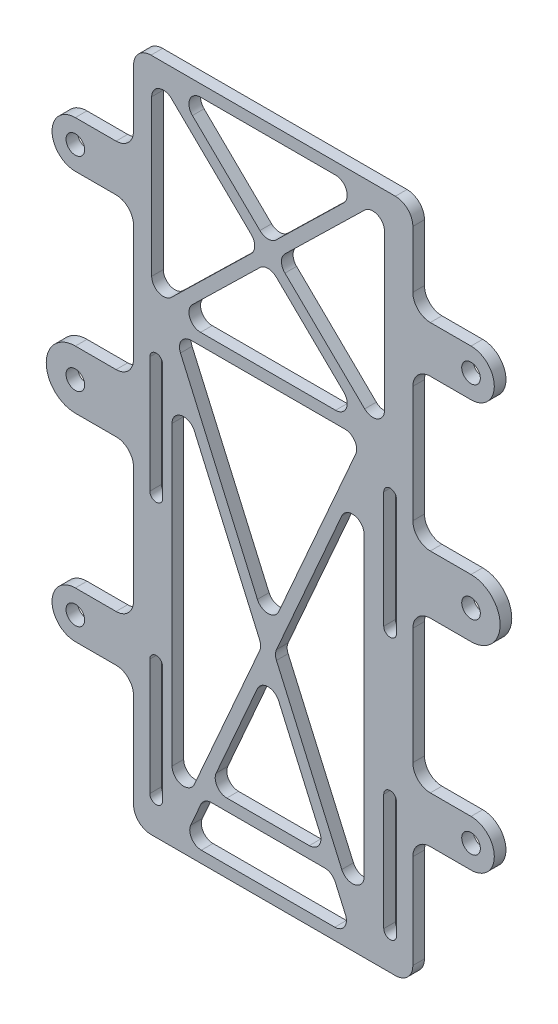
SolidWorks part; units mm, degrees
material "A-玻璃纤维"
ref_plane "前视基准面" through (0, 0, 0) normal (0, 0, 1) x (1, 0, 0)
ref_plane "上视基准面" through (0, 0, 0) normal (0, 1, 0) x (1, 0, 0)
ref_plane "右视基准面" through (0, 0, 0) normal (1, 0, 0) x (0, 0, -1)
sketch "草图1" plane through (0, 0, 0) normal (0, 0, 1) x (1, 0, 0)
  line L0 (-20.1, -32) -> (-20.1, -52) construction
  line L1 (24, 58) -> (-24, 58)
  line L2 (24, 58) -> (24, -58)
  line L3 (24, -58) -> (-24, -58)
  line L4 (-24, 58) -> (-24, -58)
  line L5 (24, 58) -> (-24, -58) construction
  line L6 (24, -58) -> (-24, 58) construction
  line L7 (-19, -32) -> (-19, -52)
  line L8 (-21.2, -32) -> (-21.2, -52)
  line L9 (20.1, -32) -> (20.1, -52) construction
  line L10 (19, -32) -> (19, -52)
  line L11 (21.2, -32) -> (21.2, -52)
  line L12 (-20.1, 13) -> (-20.1, -7) construction
  line L13 (-19, 13) -> (-19, -7)
  line L14 (-21.2, 13) -> (-21.2, -7)
  line L15 (20.1, 13) -> (20.1, -7) construction
  line L16 (19, 13) -> (19, -7)
  line L17 (21.2, 13) -> (21.2, -7)
  line L18 (0, 97.0381) -> (0, -100.4678) construction
  arc A0 (-19, -32) -> (-21.2, -32) centre (-20.1, -32) ccw
  arc A1 (-21.2, -52) -> (-19, -52) centre (-20.1, -52) ccw
  arc A2 (19, -32) -> (21.2, -32) centre (20.1, -32) cw
  arc A3 (21.2, -52) -> (19, -52) centre (20.1, -52) cw
  arc A4 (-19, 13) -> (-21.2, 13) centre (-20.1, 13) ccw
  arc A5 (-21.2, -7) -> (-19, -7) centre (-20.1, -7) ccw
  arc A6 (19, 13) -> (21.2, 13) centre (20.1, 13) cw
  arc A7 (21.2, -7) -> (19, -7) centre (20.1, -7) cw
  point P0 (0, 0)
  point P8 (-20.1, -42)
  point P16 (20.1, -42)
  point P20 (-20.1, 3)
  point P30 (20.1, 3)
  dimension "D1" = 48
  dimension "D2" = 116
  dimension "D3" = 20
  dimension "D4" = 20
  dimension "D5" = 20.1
  dimension "D6" = 65
  dimension "D7" = 2.2
  dimension "D8" = 2.2
  dimension "D9" = 6
extrude "凸台-拉伸1" add sketch "草图1" along normal blind 2
sketch "草图3" plane through (0, 0, 2) normal (0, 0, 1) x (1, 0, 0)
  line L0 (-24, -58) -> (24, -58) construction
  line L1 (12.3424, 19) -> (-14.1024, 19)
  line L2 (15.62, 5.0055) -> (15.62, -46.0055)
  line L3 (10.5824, -56) -> (-12.3424, -56)
  line L4 (-17.38, 5.0055) -> (-17.38, -46.0055)
  line L5 (16.5, 17) -> (-16.5, -58) construction
  line L6 (16.5, -58) -> (-16.5, 17) construction
  line L7 (24, 58) -> (-24, 58) construction
  line L8 (10.7201, 56) -> (-12.4801, 56)
  line L9 (19.12, 51.8601) -> (19.12, 25.1399)
  line L10 (10.7201, 21) -> (-12.4801, 21)
  line L11 (-20.88, 51.8601) -> (-20.88, 25.1399)
  line L12 (20, 58) -> (-20, 19) construction
  line L13 (0.5162, 41.2579) -> (12.1163, 52.568)
  line L14 (20, 19) -> (-20, 58) construction
  line L15 (0.9506, -27.1435) -> (12.4131, -53.1945)
  line L16 (0.9506, -13.8565) -> (14.1731, 16.1945)
  line L17 (0.5669, -19.6945) -> (11.7894, 5.811)
  line L20 (-17.4838, 53.2921) -> (-3.7812, 39.932)
  line L21 (-13.8763, 24.432) -> (-2.2762, 35.7421)
  line L22 (-13.5494, 5.811) -> (-2.3269, -19.6945)
  line L23 (-14.1731, -53.1945) -> (-2.7106, -27.1435)
  line L24 (-13.8763, 52.568) -> (-2.2762, 41.2579)
  line L25 (-17.4838, 23.7079) -> (-3.7812, 37.068)
  line L26 (-15.9331, 16.1945) -> (-2.7106, -13.8565)
  line L27 (-13.5494, -46.811) -> (-2.3269, -21.3055)
  line L32 (0.5669, -21.3055) -> (11.7894, -46.811)
  line L35 (2.0212, 37.068) -> (15.7238, 23.7079)
  line L37 (2.0212, 39.932) -> (15.7238, 53.2921)
  line L39 (0.5162, 35.7421) -> (12.1163, 24.432)
  arc A0 (-3.7812, 39.932) -> (-3.7812, 37.068) centre (-5.1774, 38.5) cw
  arc A1 (-2.2762, 35.7421) -> (0.5162, 35.7421) centre (-0.88, 34.3101) cw
  arc A2 (2.0212, 37.068) -> (2.0212, 39.932) centre (3.4174, 38.5) cw
  arc A3 (0.5162, 41.2579) -> (-2.2762, 41.2579) centre (-0.88, 42.6899) cw
  arc A4 (19.12, 51.8601) -> (15.7238, 53.2921) centre (17.12, 51.8601) ccw
  arc A5 (10.7201, 56) -> (12.1163, 52.568) centre (10.7201, 54) cw
  arc A6 (-13.8763, 52.568) -> (-12.4801, 56) centre (-12.4801, 54) cw
  arc A7 (-17.4838, 53.2921) -> (-20.88, 51.8601) centre (-18.88, 51.8601) ccw
  arc A8 (-13.8763, 24.432) -> (-12.4801, 21) centre (-12.4801, 23) ccw
  arc A9 (-17.4838, 23.7079) -> (-20.88, 25.1399) centre (-18.88, 25.1399) cw
  arc A10 (19.12, 25.1399) -> (15.7238, 23.7079) centre (17.12, 25.1399) cw
  arc A11 (10.7201, 21) -> (12.1163, 24.432) centre (10.7201, 23) ccw
  arc A12 (14.1731, 16.1945) -> (12.3424, 19) centre (12.3424, 17) ccw
  arc A13 (11.7894, 5.811) -> (15.62, 5.0055) centre (13.62, 5.0055) cw
  arc A14 (0.5669, -21.3055) -> (0.5669, -19.6945) centre (2.3976, -20.5) cw
  arc A15 (0.9506, -13.8565) -> (-2.7106, -13.8565) centre (-0.88, -13.051) cw
  arc A16 (-2.3269, -21.3055) -> (-2.3269, -19.6945) centre (-4.1576, -20.5) ccw
  arc A17 (0.9506, -27.1435) -> (-2.7106, -27.1435) centre (-0.88, -27.949) ccw
  arc A18 (10.5824, -56) -> (12.4131, -53.1945) centre (10.5824, -54) ccw
  arc A19 (15.62, -46.0055) -> (11.7894, -46.811) centre (13.62, -46.0055) cw
  arc A20 (-13.5494, -46.811) -> (-17.38, -46.0055) centre (-15.38, -46.0055) cw
  arc A21 (-14.1731, -53.1945) -> (-12.3424, -56) centre (-12.3424, -54) ccw
  arc A22 (-15.9331, 16.1945) -> (-14.1024, 19) centre (-14.1024, 17) cw
  arc A23 (-13.5494, 5.811) -> (-17.38, 5.0055) centre (-15.38, 5.0055) ccw
  point P0 (0, -20.5)
  point P5 (0, 38.5)
  point P14 (-20.6981, 57.284)
  point P15 (19.3019, 18.284)
  point P16 (-19.3019, 18.284)
  point P17 (20.6981, 57.284)
  point P20 (-17.4153, 16.5973)
  point P21 (15.5847, -58.4027)
  point P22 (-15.5847, -58.4027)
  point P23 (17.4153, 16.5973)
  point P24 (-19.3019, 58.716)
  point P25 (20.6981, 19.716)
  point P26 (-20.6981, 19.716)
  point P27 (19.3019, 58.716)
  point P28 (-15.5847, 17.4027)
  point P29 (17.4153, -57.5973)
  point P30 (-17.4153, -57.5973)
  point P31 (15.5847, 17.4027)
  point P59 (-0.88, 37.1034)
  point P62 (0.5525, 38.5)
  point P87 (0.2125, -20.5)
  dimension "D8" = 2
  dimension "D1" = 75
  dimension "D2" = 2
  dimension "D3" = 2
  dimension "D4" = 2
  dimension "D5" = 33
  dimension "D6" = 40
  dimension "D7" = 2
extrude "切除-拉伸1" cut sketch "草图3" against normal through all
sketch "草图6" plane through (0, 0, 0) normal (0, 0, -1) x (-1, 0, 0)
  line L0 (-10.1495, -48.05) -> (11.9095, -48.05)
  line L1 (-12.4131, -53.1945) -> (-0.9506, -27.1435) construction
  line L2 (2.7106, -27.1435) -> (14.1731, -53.1945) construction
  line L4 (-10.1495, -48.05) -> (-9.2695, -46.05)
  line L5 (-9.2695, -46.05) -> (11.0295, -46.05)
  line L6 (11.0295, -46.05) -> (11.9095, -48.05)
  line L7 (24, -58) -> (-24, -58) construction
  dimension "D1" = 9.95
  dimension "D2" = 2
extrude "凸台-拉伸4" add sketch "草图6" against normal blind 2
fillet "圆角2" radius 2 4 edges at (-11.0295, -46.05, 1) (9.2695, -46.05, 1) (-11.9095, -48.05, 1) (10.1495, -48.05, 1)
sketch "草图7" plane through (0, 0, 0) normal (0, 0, -1) x (-1, 0, 0)
  line L1 (24, -35.8) -> (34, -35.8)
  line L2 (24, 58) -> (24, -58) construction
  line L3 (34, -27.8) -> (24, -27.8)
  line L4 (24, -27.8) -> (24, -35.8)
  line L5 (24, -58) -> (-24, -58) construction
  arc A0 (34, -35.8) -> (34, -27.8) centre (34, -31.8) ccw
  circle A1 centre (34, -31.8) radius 1.6
  dimension "D1" = 3.2
  dimension "D4" = 4
  dimension "D2" = 26.2
  dimension "D3" = 34
extrude "凸台-拉伸5" add sketch "草图7" against normal blind 2
pattern_linear "阵列(线性)1" count 2 spacing 70 along (0, 1, 0) of "凸台-拉伸5"
mirror "镜向1" about plane through (0, 0, 0) normal (1, 0, 0) of "阵列(线性)1", "凸台-拉伸5"
fillet "圆角4" radius 3 4 edges at (24, 58, 1) (-24, 58, 1) (24, -58, 1) (-24, -58, 1)
fillet "圆角5" radius 3 8 edges at (24, -27.8, 1) (24, -35.8, 1) (24, 34.2, 1) (24, 42.2, 1) (-24, 42.2, 1) (-24, -27.8, 1) (-24, -35.8, 1) (-24, 34.2, 1)
sketch "草图8" plane through (0, 0, 2) normal (0, 0, 1) x (1, 0, 0)
  line L0 (-34, -1.8) -> (-24, -1.8)
  line L1 (-24, 31.2) -> (-24, -24.8) construction
  line L2 (-34, 8.2) -> (-24, 8.2)
  line L3 (-24, 8.2) -> (-24, -1.8)
  line L4 (0, 14.4251) -> (0, -6.9531) construction
  line L5 (24, 8.2) -> (24, -1.8)
  line L6 (34, 8.2) -> (24, 8.2)
  line L7 (34, -1.8) -> (24, -1.8)
  arc A0 (-34, 8.2) -> (-34, -1.8) centre (-34, 3.2) ccw
  circle A1 centre (-34, 38.2) radius 1.6 construction
  circle A2 centre (-34, 3.2) radius 1.6
  circle A3 centre (34, 3.2) radius 1.6
  arc A4 (34, 8.2) -> (34, -1.8) centre (34, 3.2) cw
  dimension "D1" = 10
  dimension "D2" = 35
  dimension "D4" = 3.2
  dimension "D3" = 0
extrude "凸台-拉伸6" add sketch "草图8" against normal up to surface (2 mm away) up to face at (-0.88, -51.6781, 0)
fillet "圆角6" radius 3 4 edges at (-24, -1.8, 1) (-24, 8.2, 1) (24, 8.2, 1) (24, -1.8, 1)
